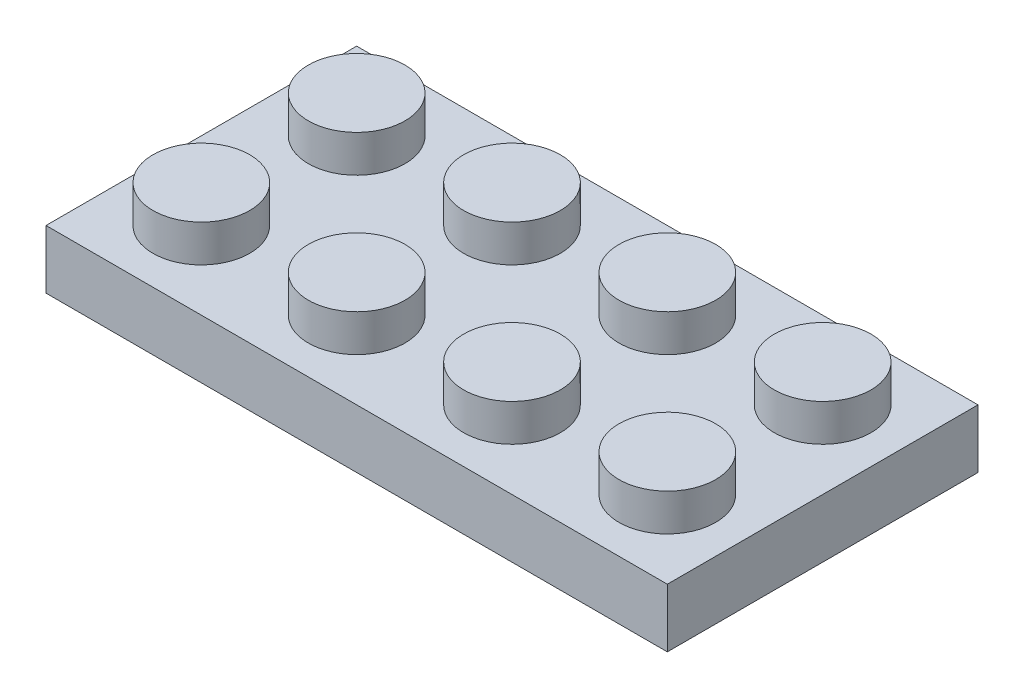
SolidWorks part; units mm, degrees
ref_plane "Front Plane" through (0, 0, 0) normal (0, 0, 1) x (1, 0, 0)
ref_plane "Top Plane" through (0, 0, 0) normal (0, 1, 0) x (1, 0, 0)
ref_plane "Right Plane" through (0, 0, 0) normal (1, 0, 0) x (0, 0, -1)
sketch "Sketch1" plane through (0, 0, 0) normal (0, 1, 0) x (1, 0, 0)
  line L1 (0, 0) -> (31.8, 0)
  line L2 (0, 0) -> (0, -15.9)
  line L3 (0, -15.9) -> (31.8, -15.9)
  line L4 (31.8, 0) -> (31.8, -15.9)
  dimension "D1" = 31.8
  dimension "D2" = 15.9
extrude "Boss-Extrude1" add sketch "Sketch1" along normal blind 3
sketch "Sketch2" plane through (0, 3, 0) normal (0, 1, 0) x (1, 0, 0)
  line L0 (0, -15.9) -> (31.8, -15.9) construction
  line L1 (31.8, 0) -> (0, 0) construction
  line L2 (0, 0) -> (0, -15.9) construction
  line L3 (31.8, -15.9) -> (31.8, 0) construction
  circle A0 centre (3.975, -3.975) radius 2.475
  circle A1 centre (11.925, -3.975) radius 2.475
  circle A2 centre (19.875, -3.975) radius 2.475
  circle A3 centre (27.825, -3.975) radius 2.475
  circle A4 centre (27.825, -11.925) radius 2.475
  circle A5 centre (19.875, -11.925) radius 2.475
  circle A6 centre (11.925, -11.925) radius 2.475
  circle A7 centre (3.975, -11.925) radius 2.475
  dimension "D1" = 4.95
  dimension "D3" = 3.975
  dimension "D4" = 4.95
  dimension "D5" = 4.95
  dimension "D6" = 4.95
  dimension "D7" = 4.95
  dimension "D8" = 4.95
  dimension "D9" = 4.95
  dimension "D10" = 4.95
  dimension "D11" = 3.975
  dimension "D12" = 3.975
  dimension "D13" = 3.975
  dimension "D14" = 7.95
  dimension "D2" = 3.975
  dimension "D15" = 7.95
  dimension "D16" = 3.975
  dimension "D17" = 3.975
  dimension "D18" = 3.975
  dimension "D19" = 3.975
  dimension "D20" = 3.975
  dimension "D21" = 3.975
  dimension "D22" = 3.975
  dimension "D23" = 7.95
  dimension "D24" = 7.95
extrude "Boss-Extrude2" add sketch "Sketch2" along normal blind 1.9
sketch "Sketch3" plane through (0, 0, 0) normal (0, -1, 0) x (1, 0, 0)
  line L0 (1.5, 14.4) -> (1.5, 1.5)
  line L1 (1.5, 1.5) -> (30.3, 1.5)
  line L2 (30.3, 1.5) -> (30.3, 14.4)
  line L3 (30.3, 14.4) -> (1.5, 14.4)
  line L4 (0, 0) -> (0, 15.9) construction
  line L5 (0, 15.9) -> (31.8, 15.9) construction
  line L6 (31.8, 15.9) -> (31.8, 0) construction
  line L7 (31.8, 0) -> (0, 0) construction
  dimension "D1" = 1.5
  dimension "D2" = 1.5
  dimension "D3" = 1.5
  dimension "D4" = 1.5
extrude "Cut-Extrude1" cut sketch "Sketch3" against normal blind 2
